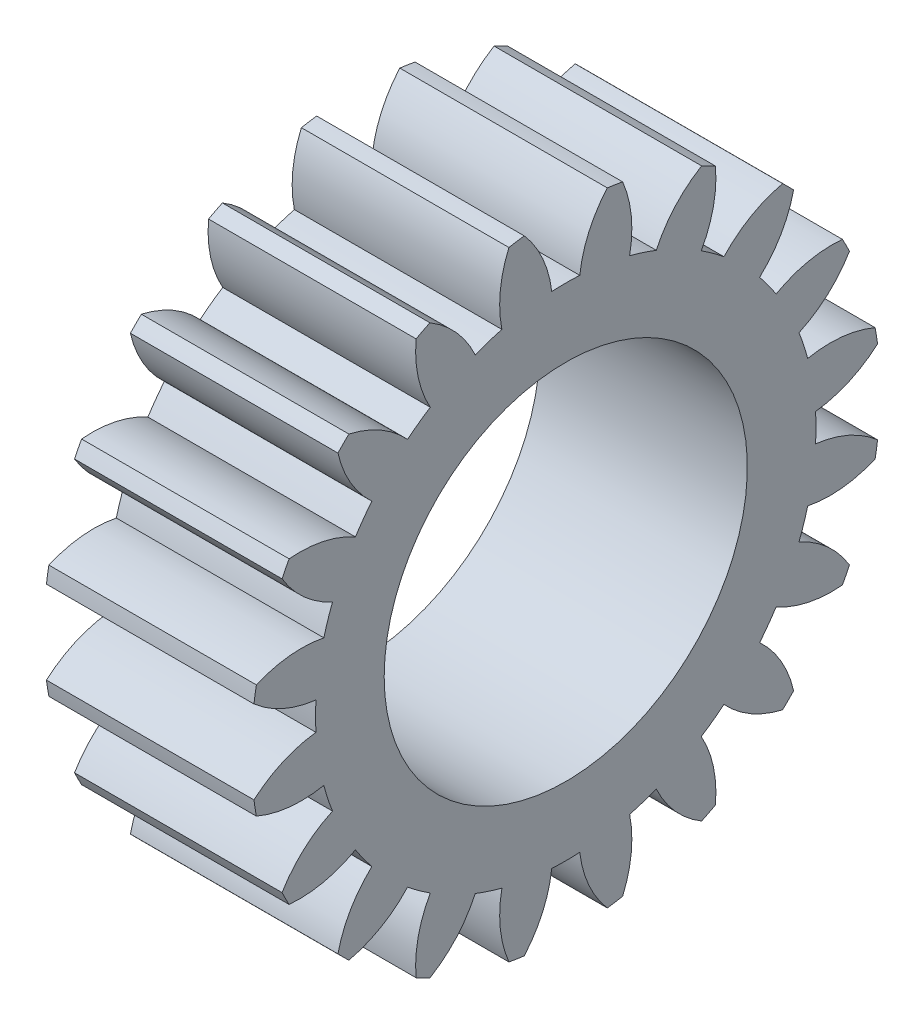
SolidWorks part; units mm, degrees
ref_plane "Plane1" through (0, 0, 0) normal (0, 0, 1) x (1, 0, 0)
ref_plane "Plane2" through (0, 0, 0) normal (0, 1, 0) x (1, 0, 0)
ref_plane "Plane3" through (0, 0, 0) normal (1, 0, 0) x (0, 0, -1)
sketch "HoldingSke" plane through (0, 0, 0) normal (0, 1, 0) x (1, 0, 0)
  line L0 (0, 0) -> (0.0134, -0.0049)
  line L1 (-15, 0) -> (100, 0) construction
  line L2 (0, 0) -> (-2.1039, 2.3779)
  line L3 (0, 0) -> (-11.863, 4.5341)
  line L4 (0, 0) -> (8.1152, 2.9537)
  line L5 (0, 0) -> (-46.8476, -17.4728)
  line L6 (0, 0) -> (-421.1131, -284.1262)
  line L7 (-2.1039, 2.3779) -> (107.2427, 498.47)
  line L8 (-76.2, 54.61) -> (-56.7, 54.61)
  line L9 (-71.009, 38.7566) -> (-53.1078, 45.2721)
  line L10 (-76.2, 71.12) -> (104.1128, 71.12)
  line L11 (0, 0) -> (-508, 0)
  line L12 (-76.2, 101.6) -> (-74, 101.6)
  line L13 (24.9733, 27.94) -> (52.9518, 28.4284)
  line L14 (24.9733, 27.94) -> (24.9743, 27.94)
  line L15 (24.9733, 27.94) -> (100.4006, 29.5858)
  line L16 (-63.627, -70) -> (-12.827, -70)
  circle A0 centre (0, 0) radius 250
  circle A1 centre (0, 0) radius 37.5
  circle A2 centre (0, 0) radius 37.5
  circle A3 centre (0, 0) radius 250
  dimension "MHD" = 75
  dimension "Hub_dia" = 75
  dimension "Bore" = 500
  dimension "MBD" = 500
  dimension "Num_teeth" = 20
  dimension "Pitch" = 0.0143
  dimension "Overall_len" = 50
  dimension "Show_teeth" = 20
  dimension "Thickness" = 508
  dimension "OAL" = 508.0001
  dimension "T_dim" = 19.5
  dimension "Ap" = 20
  dimension "H" = 19.05
  dimension "Pitch_radius" = 180.3128
  dimension "Width" = 508
  dimension "Backlash" = 2.2
  dimension "Addendum_fac" = 1
  dimension "Dedendum_fac" = 1.25
  dimension "Clearance_fac" = 0.25
  dimension "Dedendum_add" = 0.001
  dimension "Module" = 70
sketch "BasProSke" plane through (0, 0, 0) normal (0, 1, 0) x (1, 0, 0)
  line L0 (-10, 0) -> (60, 0) construction
  line L1 (0, 0) -> (0, 770)
  line L2 (0, 0) -> (508, 0)
  line L3 (508, 0) -> (508, 770)
  line L4 (508, 770) -> (0, 770)
  dimension "Thickness" = 508
  dimension "Diameter" = 1540
revolve "Base-Revolve" add sketch "BasProSke" angle 360 about L0
sketch "TooCutSke" plane through (0, 0, 0) normal (1, 0, 0) x (0, 0, -1)
  line L1 (0, 0) -> (0, 107) construction
  line L2 (0, 0) -> (-58.7697, 697.5286) construction
  line L3 (0, 0) -> (-218.4246, 1379.0785) construction
  line L4 (-58.7697, 697.5286) -> (-109.2123, 689.5393) construction
  arc A0 (34.2977, 611.538) -> (-34.2977, 611.538) centre (0, 0) ccw
  arc A1 (101.687, 763.2816) -> (-101.687, 763.2816) centre (0, 0) ccw
  circle A2 centre (0, 0) radius 700 construction
  circle A3 centre (0, 0) radius 657.7848 construction
  arc A4 (-34.2977, 611.538) -> (-101.687, 763.2816) centre (-312.386, 578.8746) ccw
  arc A5 (101.687, 763.2816) -> (34.2977, 611.538) centre (312.386, 578.8746) ccw
  dimension "Root_dia" = 1224.998
  dimension "Overcut_dia" = 1540.0508
  dimension "Pitch_dia" = 1400
  dimension "Base_dia" = 1315.5697
  dimension "Flank_rad" = 280
  dimension "Half_ang" = 9
  dimension "Half_CT" = 51.0714
extrude "ToothCut" cut sketch "TooCutSke" along normal through all
fillet "Breaks" [suppressed] radius 1.4
fillet "RootFillets" [suppressed] radius 17.501
pattern_circular "TeethCuts" count 20 every 18 about axis through (-10, 0, 0) along (1, 0, 0) of "ToothCut", "RootFillets", "Breaks"
sketch "HubNeaOneSke" plane through (0, 0, 0) normal (-1, 0, 0) x (0, 0, 1)
  circle A0 centre (0, 0) radius 37.5
  dimension "Diameter" = 75
extrude "HubNearOne" [suppressed] add sketch "HubNeaOneSke" along normal blind 38.0001
sketch "HubNeaBotSke" plane through (0, 0, 0) normal (-1, 0, 0) x (0, 0, 1)
  circle A0 centre (0, 0) radius 37.5
  dimension "Diameter" = 75
extrude "HubNearBoth" [suppressed] add sketch "HubNeaBotSke" along normal blind 19
ref_plane "FarPln" through (508, 0, 0) normal (1, 0, 0) x (0, 0, -1)
sketch "HubFarSke" plane through (508, 0, 0) normal (1, 0, 0) x (0, 0, -1)
  circle A0 centre (0, 0) radius 37.5
  dimension "Diameter" = 75
extrude "HubFar" [suppressed] add sketch "HubFarSke" along normal blind 19
sketch "BorSke" plane through (0, 0, 0) normal (1, 0, 0) x (0, 0, -1)
  circle A0 centre (0, 0) radius 250
  dimension "Diameter" = 500
extrude "Bore" cut sketch "BorSke" along normal mid plane 1016.0001
sketch "KeySke" plane through (0, 0, 0) normal (1, 0, 0) x (0, 0, -1)
  line L0 (-50, 0) -> (-50, 269.5)
  line L1 (-50, 269.5) -> (50, 269.5)
  line L2 (50, 269.5) -> (50, 0)
  line L3 (0, 0) -> (0, 34) construction
  line L4 (-50, 0) -> (50, 0)
  dimension "Offset" = 269.5
  dimension "Width" = 100
extrude "Keyway" [suppressed] cut sketch "KeySke" along normal mid plane 1016.0001
pattern_circular "Keyway2" [suppressed] count 2 every 90 about axis through (-10, 0, 0) along (1, 0, 0)
sketch "Sketch1" plane through (0, 0, 0) normal (-1, 0, 0) x (0, 0, 1)
  circle A0 centre (0, 0) radius 444.5
extrude "Cut-Extrude1" cut sketch "Sketch1" against normal up to surface (508 mm away) up to face at (508, 0, 250)
equation "' \"Module@HoldingSke\" = 6.35"
equation "' \"Num_teeth@HoldingSke\" = 12"
equation "' \"Ap@HoldingSke\" =  20"
equation "' \"Ap@HoldingSke\" = 20"
equation "' \"Width@HoldingSke\" = 0.5 * 25.4"
equation "' \"Hub_dia@HoldingSke\"= 1 * 25.4"
equation "' \"Hub_dia@HoldingSke\" = 1 * 25.4"
equation "' \"Overall_len@HoldingSke\" = 1.0 * 25.4"
equation "' \"Bore@HoldingSke\" = 0.75 * 25.4"
equation "' \"T_dim@HoldingSke\" = 0.1 * 25.4"
equation "' \"Width@KeySke\" = 0.25 * 25.4"
equation "' \"Show_teeth@HoldingSke\" = 13"
equation "' \"Backlash@HoldingSke\" = 0.009 * 25.4"
equation "' \"Addendum_fac@HoldingSke\" = 1.0"
equation "' \"Dedendum_fac@HoldingSke\" = 1.25"
equation "' \"Dedendum_add@HoldingSke\" = 0.00005 * 25.4"
equation "' \"Clearance_fac@HoldingSke\" = 0.25"
equation "\"Pitch@HoldingSke\" = 1 / \"Module@HoldingSke\""
equation "\"Overcut_dia@TooCutSke\" = (\"Num_teeth@HoldingSke\" + 2 * \"Addendum_fac@HoldingSke\") / \"Pitch@HoldingSke\" + 0.002 * 25.4"
equation "\"Pitch_dia@TooCutSke\" = \"Num_teeth@HoldingSke\" / \"Pitch@HoldingSke\""
equation "\"Base_dia@TooCutSke\" = \"Num_teeth@HoldingSke\" / \"Pitch@HoldingSke\" * cos((\"Ap@HoldingSke\"  * 3.14159265 / 180))"
equation "\"Root_dia@TooCutSke\" = (\"Num_teeth@HoldingSke\" + 2) / \"Pitch@HoldingSke\" - 2 * (\"Addendum_fac@HoldingSke\" + \"Dedendum_fac@HoldingSke\") / \"Pitch@HoldingSke\" - \"Dedendum_add@HoldingSke\" * 2"
equation "\"Half_ang@TooCutSke\" = 180 / \"Num_teeth@HoldingSke\""
equation "\"Half_CT@TooCutSke\" = \"Num_teeth@HoldingSke\" / \"Pitch@HoldingSke\" * sin((3.14159265 / 2 / \"Num_teeth@HoldingSke\")) / 2 - 7 * \"Backlash@HoldingSke\" / 4"
equation "\"Flank_rad@TooCutSke\" = \"Num_teeth@HoldingSke\" / \"Pitch@HoldingSke\" / 5"
equation "\"Radius@RootFillets\" = \"Clearance_fac@HoldingSke\" / \"Pitch@HoldingSke\" + \"Dedendum_add@HoldingSke\""
equation "\"Break_rad@Breaks\" = 0.02 / \"Pitch@HoldingSke\""
equation "\"Thickness@HoldingSke\" = \"Width@HoldingSke\""
equation "\"OAL@HoldingSke\" = \"Thickness@HoldingSke\""
equation "\"MHD@HoldingSke\" = (\"Num_teeth@HoldingSke\" + 2) / \"Pitch@HoldingSke\" - 2 * (\"Addendum_fac@HoldingSke\" + \"Dedendum_fac@HoldingSke\")  / \"Pitch@HoldingSke\" - \"Dedendum_add@HoldingSke\" * 2"
equation "\"MBD@HoldingSke\" = (\"Num_teeth@HoldingSke\" + 2) / \"Pitch@HoldingSke\" - 2 * (\"Addendum_fac@HoldingSke\" + \"Dedendum_fac@HoldingSke\")  / \"Pitch@HoldingSke\" - \"Dedendum_add@HoldingSke\" * 2 - 0.002 * 25.4"
equation "\"MHD@HoldingSke\" = ((sgn( \"MHD@HoldingSke\" - \"Hub_dia@HoldingSke\" )-1)*( \"MHD@HoldingSke\" - \"Hub_dia@HoldingSke\" ))/-2+ \"Hub_dia@HoldingSke\""
equation "\"MBD@HoldingSke\" = ((sgn( \"MBD@HoldingSke\" - \"Bore@HoldingSke\" )-1)*( \"MBD@HoldingSke\" - \"Bore@HoldingSke\" ))/-2+ \"Bore@HoldingSke\""
equation "\"OAL@HoldingSke\" = ((sgn( \"OAL@HoldingSke\" - \"Overall_len@HoldingSke\" )+1)*( \"OAL@HoldingSke\" - \"Overall_len@HoldingSke\" ))/2 + \"Overall_len@HoldingSke\" + 0.000002 * 25.4"
equation "\"Num_teeth@TeethCuts\" = int( \"Show_teeth@HoldingSke\" ) + 1"
equation "\"Num_teeth@TeethCuts\" = ((sgn( \"Num_teeth@TeethCuts\" - \"Num_teeth@HoldingSke\" )-1)*( \"Num_teeth@TeethCuts\" - \"Num_teeth@HoldingSke\" ))/-2+ \"Num_teeth@HoldingSke\""
equation "\"Num_teeth@TeethCuts\" = ((sgn( \"Num_teeth@TeethCuts\" - 2.0)+1)*( \"Num_teeth@TeethCuts\" - 2.0))/2 +2.0"
equation "\"Angle@TeethCuts\" = 360.0 / \"Num_teeth@HoldingSke\""
equation "\"Diameter@BasProSke\" = (\"Num_teeth@HoldingSke\" + 2 * \"Addendum_fac@HoldingSke\") / \"Pitch@HoldingSke\""
equation "\"Thickness@BasProSke\"  = \"Thickness@HoldingSke\""
equation "' \"Fillet_rad@BasProSke\" =  \"Thickness@HoldingSke\" * 0.05"
equation "' \"Fillet_rad@BasProSke\" = \"Thickness@HoldingSke\" * 0.05"
equation "\"MHD@HoldingSke\" = ((sgn( \"MHD@HoldingSke\" - \"Root_dia@TooCutSke\" )-1)*( \"MHD@HoldingSke\" - \"Root_dia@TooCutSke\" ))/-2+ \"Root_dia@TooCutSke\""
equation "\"Diameter@HubNeaOneSke\" = \"MHD@HoldingSke\""
equation "\"Length@HubNearOne\" = \"OAL@HoldingSke\" - \"Thickness@BasProSke\""
equation "\"Diameter@HubNeaBotSke\" = \"MHD@HoldingSke\""
equation "\"Length@HubNearBoth\" = ( \"OAL@HoldingSke\" - \"Thickness@BasProSke\" ) / 2.0"
equation "\"Thickness@FarPln\" = \"Thickness@BasProSke\""
equation "\"Diameter@HubFarSke\" = \"MHD@HoldingSke\""
equation "\"Length@HubFar\" = ( \"OAL@HoldingSke\" - \"Thickness@BasProSke\" ) / 2.0"
equation "\"Diameter@BorSke\" = \"MBD@HoldingSke\""
equation "\"D1@Bore\" = \"OAL@HoldingSke\" * 2.0"
equation "\"D1@Keyway\" = \"OAL@HoldingSke\" * 2.0"
equation "\"Offset@KeySke\" = \"T_dim@HoldingSke\" + \"MBD@HoldingSke\" / 2.0"
